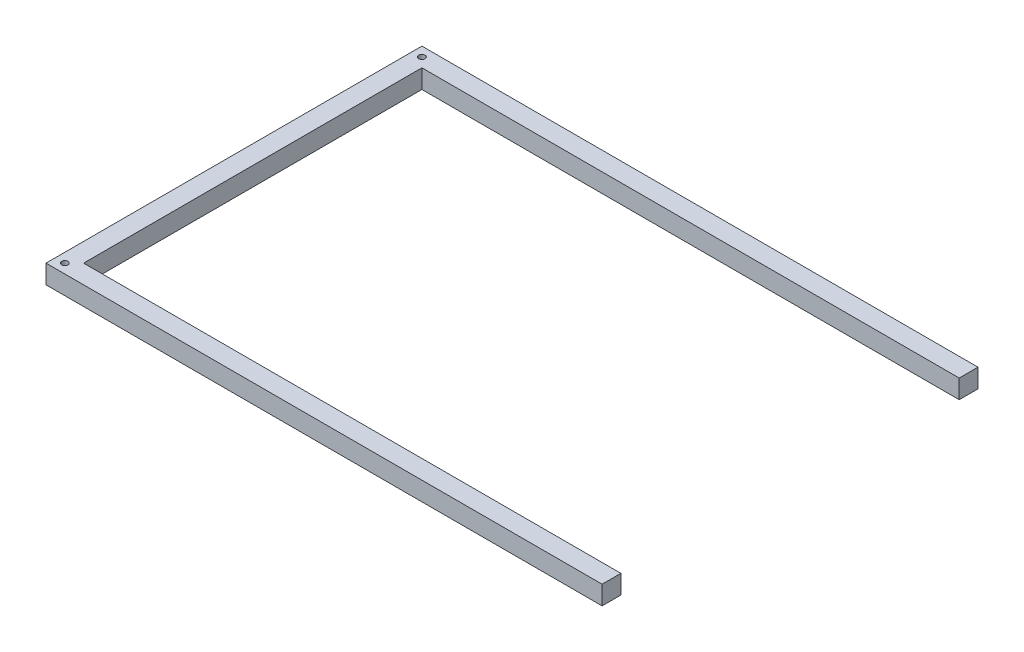
SolidWorks part; units mm, degrees
ref_plane "Front Plane" through (0, 0, 0) normal (0, 0, 1) x (1, 0, 0)
ref_plane "Top Plane" through (0, 0, 0) normal (0, 1, 0) x (1, 0, 0)
ref_plane "Right Plane" through (0, 0, 0) normal (1, 0, 0) x (0, 0, -1)
sketch "Sketch1" plane through (0, 0, 0) normal (0, 1, 0) x (1, 0, 0)
  line L0 (42.8625, 26.9875) -> (42.8625, 29.9875)
  line L1 (-42.8625, -26.9875) -> (42.8625, -26.9875)
  line L2 (-42.8625, -26.9875) -> (-42.8625, 26.9875)
  line L3 (-42.8625, 26.9875) -> (42.8625, 26.9875)
  line L4 (-45.8625, 29.9875) -> (-42.8625, 26.9875) construction
  line L5 (-42.8625, -26.9875) -> (42.8625, 26.9875) construction
  line L6 (-42.8625, 26.9875) -> (42.8625, -26.9875) construction
  line L7 (42.8625, 29.9875) -> (-45.8625, 29.9875)
  line L8 (-45.8625, 29.9875) -> (-45.8625, -29.9875)
  line L9 (-45.8625, -29.9875) -> (42.8625, -29.9875)
  line L10 (42.8625, -29.9875) -> (42.8625, -26.9875)
  line L11 (-42.8625, -26.9875) -> (-45.8625, -29.9875) construction
  circle A0 centre (-44.3625, 28.4875) radius 0.5
  circle A1 centre (-44.3625, -28.4875) radius 0.5
  point P0 (0, 0)
  dimension "D6" = 1
  dimension "D7" = 1
  dimension "D1" = 85.725
  dimension "D2" = 53.975
  dimension "D3" = 3
  dimension "D4" = 3
  dimension "D5" = 3
extrude "Boss-Extrude1" add sketch "Sketch1" along normal blind 3
